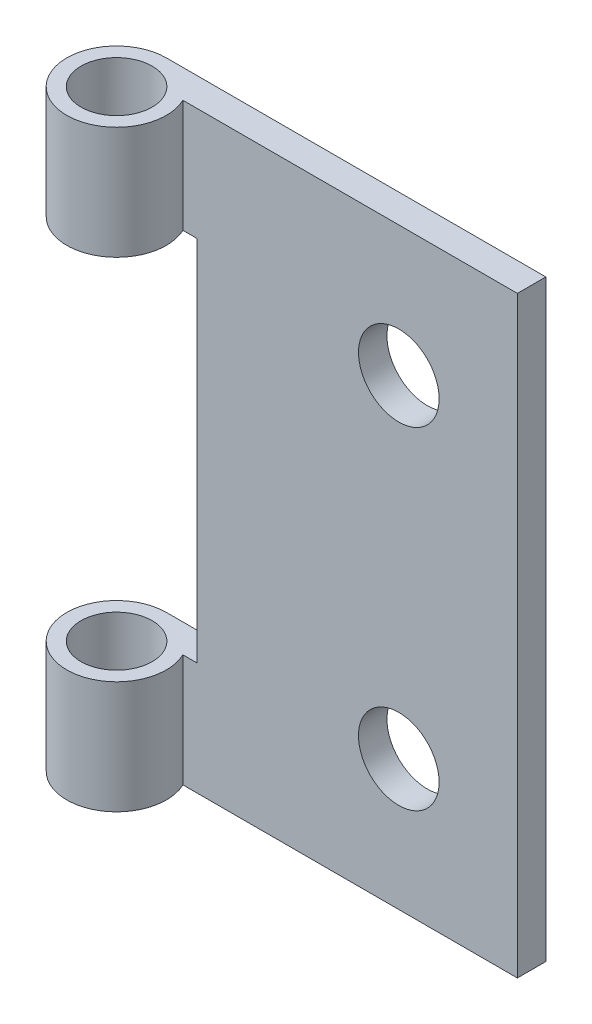
SolidWorks part; units mm, degrees
ref_plane "前视基准面" through (0, 0, 0) normal (0, 0, 1) x (1, 0, 0)
ref_plane "上视基准面" through (0, 0, 0) normal (0, 1, 0) x (1, 0, 0)
ref_plane "右视基准面" through (0, 0, 0) normal (1, 0, 0) x (0, 0, -1)
sketch "草图1" plane through (0, 0, 0) normal (0, 0, 1) x (1, 0, 0)
  line L0 (0, 0) -> (-13919.3604, 0) construction
  line L1 (0, 12.5) -> (13.5, 12.5)
  line L2 (0, 12.5) -> (0, -12.5)
  line L3 (0, -12.5) -> (13.5, -12.5)
  line L4 (13.5, 12.5) -> (13.5, -12.5)
  line L5 (0, 0) -> (0, 13919.3604) construction
  line L7 (0, 12.5) -> (-2.5, 12.5)
  line L8 (0, 12.5) -> (0, 7.75)
  line L9 (0, 7.75) -> (-2.5, 7.75)
  line L10 (-2.5, 12.5) -> (-2.5, 7.75)
  line L11 (0, -12.5) -> (-2.5, -12.5)
  line L12 (0, -12.5) -> (0, -7.75)
  line L13 (0, -7.75) -> (-2.5, -7.75)
  line L14 (-2.5, -12.5) -> (-2.5, -7.75)
  dimension "D1" = 13.5
  dimension "D2" = 25
  dimension "D3" = 2.5
  dimension "D4" = 15.5
extrude "凸台-拉伸1" add sketch "草图1" along normal blind 1.2 contours L4 L1 L2 L3 | L7 L10 L9 L2 | L11 L14 L13 L12
sketch "草图2" plane through (0, 0, 1.2) normal (0, 0, 1) x (1, 0, 0)
  line L0 (8.5, 7) -> (8.5, -7) construction
  line L1 (13.5, 12.5) -> (13.5, -12.5) construction
  line L2 (0, 0) -> (-50000, 0) construction
  line L3 (0, 7.75) -> (0, -7.75) construction
  circle A0 centre (8.5, 7) radius 1.7
  circle A1 centre (8.5, -7) radius 1.7
  dimension "D1" = 3.4
  dimension "D3" = 8.5
  dimension "D2" = 14
extrude "切除-拉伸1" cut sketch "草图2" against normal blind 1.2
sketch "草图3" plane through (0, -12.5, 0) normal (0, -1, 0) x (1, 0, 0)
  line L0 (0, 1.2) -> (0, 0) construction
  line L2 (-2.5, 0) -> (13.5, 0) construction
  circle A0 centre (-2.5, 2.1) radius 2.1
  dimension "D1" = 4.2
  dimension "D2" = 2.5
extrude "凸台-拉伸2" add sketch "草图3" against normal blind 25
sketch "草图4" plane through (0, -12.5, 0) normal (0, -1, 0) x (1, 0, 0)
  circle A0 centre (-2.5, 2.1) radius 1.5
  arc A1 (-0.6026, 1.2) -> (-2.5, 0) centre (-2.5, 2.1) ccw construction
  dimension "D1" = 3
extrude "切除-拉伸2" cut sketch "草图4" against normal blind 25
sketch "草图5" plane through (0, 0, 1.2) normal (0, 0, 1) x (1, 0, 0)
  line L1 (0, 7.75) -> (-5, 7.75)
  line L2 (0, 7.75) -> (0, -7.75)
  line L3 (0, -7.75) -> (-5, -7.75)
  line L4 (-5, 7.75) -> (-5, -7.75)
  dimension "D1" = 5
extrude "切除-拉伸3" cut sketch "草图5" against normal mid plane 15
